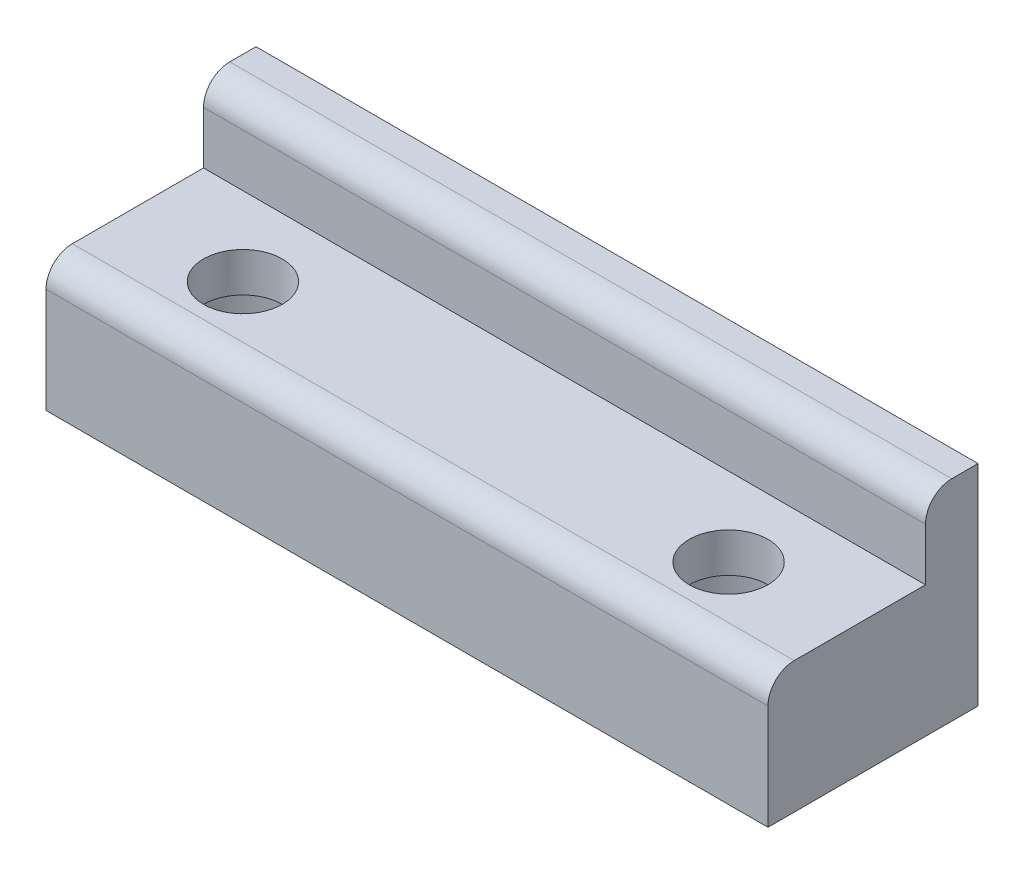
SolidWorks part; units mm, degrees
ref_plane "Спереди" through (0, 0, 0) normal (0, 0, 1) x (1, 0, 0)
ref_plane "Сверху" through (0, 0, 0) normal (0, 1, 0) x (1, 0, 0)
ref_plane "Справа" through (0, 0, 0) normal (1, 0, 0) x (0, 0, -1)
sketch "Эскиз1" plane through (0, 0, 0) normal (0, 1, 0) x (1, 0, 0)
  line L1 (0, 0) -> (27.5, 0)
  line L2 (0, 0) -> (0, 8)
  line L3 (0, 8) -> (27.5, 8)
  line L4 (27.5, 0) -> (27.5, 8)
  dimension "D1" = 8
  dimension "D2" = 27.5
extrude "Бобышка-Вытянуть1" add sketch "Эскиз1" along normal blind 5
sketch "Эскиз2" plane through (0, 5, 0) normal (0, 1, 0) x (1, 0, 0)
  line L0 (27.5, 0) -> (27.5, 8) construction
  line L1 (0, 8) -> (27.5, 8)
  line L2 (0, 8) -> (0, 6)
  line L3 (0, 6) -> (27.5, 6)
  line L4 (27.5, 8) -> (27.5, 6)
  dimension "D1" = 2
extrude "Бобышка-Вытянуть2" add sketch "Эскиз2" along normal blind 3
sketch "Эскиз3" plane through (0, 5, 0) normal (0, 1, 0) x (1, 0, 0)
  line L0 (0, 3) -> (27.5, 3) construction
  line L1 (0, 6) -> (0, 0) construction
  line L2 (27.5, 0) -> (27.5, 6) construction
  circle A0 centre (4.5, 3) radius 1.5
  circle A1 centre (23, 3) radius 1.5
  dimension "D3" = 3
  dimension "D1" = 4.5
  dimension "D2" = 4.5
extrude "Вырез-Вытянуть1" cut sketch "Эскиз3" against normal through all
sketch "Эскиз4" plane through (0, 0, 0) normal (0, -1, 0) x (-1, 0, 0)
  circle A0 centre (-4.5, 3) radius 2.95
  circle A1 centre (-23, 3) radius 2.95
  dimension "D1" = 5.9
extrude "Вырез-Вытянуть6" cut sketch "Эскиз4" against normal blind 3.5
fillet "Скругление1" radius 1 1 edges at (13.75, 8, -6)
fillet "Скругление2" radius 1 1 edges at (13.75, 5, 0)
